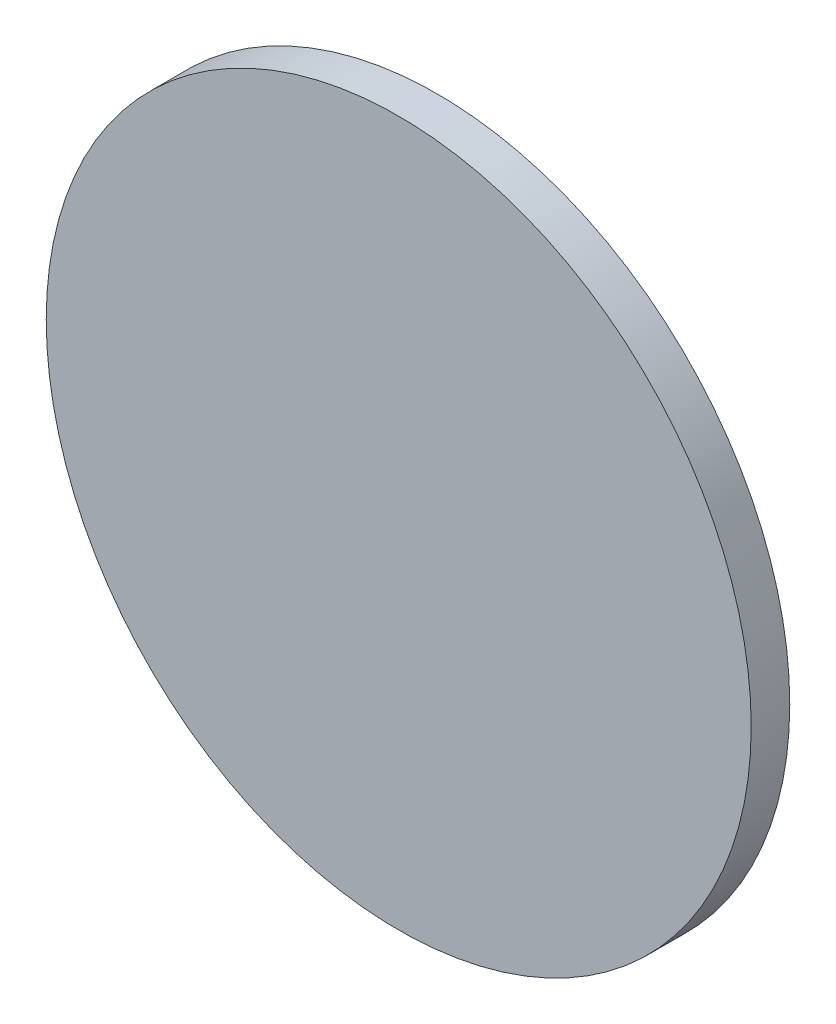
SolidWorks part; units mm, degrees
ref_plane "Front Plane" through (0, 0, 0) normal (0, 0, 1) x (1, 0, 0)
ref_plane "Top Plane" through (0, 0, 0) normal (0, 1, 0) x (1, 0, 0)
ref_plane "Right Plane" through (0, 0, 0) normal (1, 0, 0) x (0, 0, -1)
sketch "Sketch1" plane through (0, 0, 0) normal (0, 0, 1) x (1, 0, 0)
  circle A0 centre (0, 0) radius 64
  dimension "D1" = 128
extrude "Boss-Extrude1" add sketch "Sketch1" along normal blind 7
